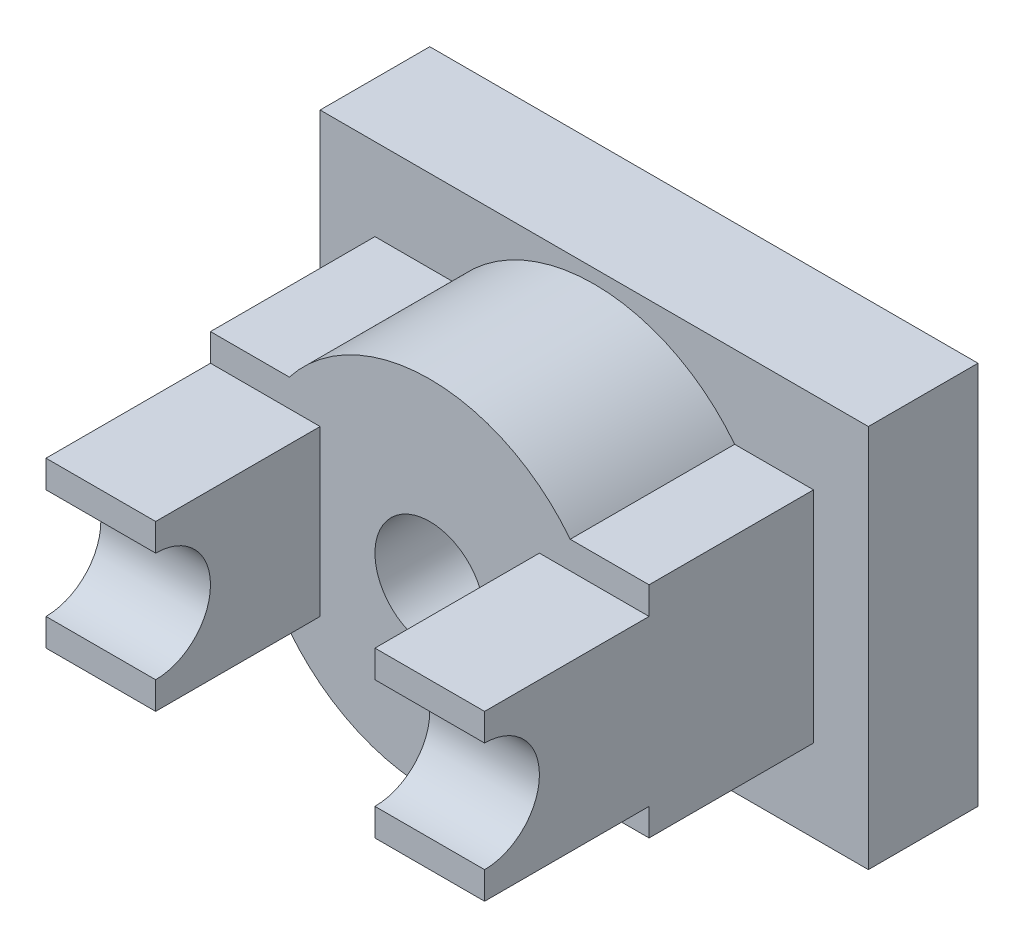
SolidWorks part; units mm, degrees
ref_plane "前基準面" through (0, 0, 0) normal (0, 0, 1) x (1, 0, 0)
ref_plane "上基準面" through (0, 0, 0) normal (0, 1, 0) x (1, 0, 0)
ref_plane "右基準面" through (0, 0, 0) normal (1, 0, 0) x (0, 0, -1)
sketch "草圖1" plane through (0, 0, 0) normal (0, 0, 1) x (1, 0, 0)
  line L1 (-50, 35) -> (50, 35)
  line L2 (-50, 35) -> (-50, -35)
  line L3 (-50, -35) -> (50, -35)
  line L4 (50, 35) -> (50, -35)
  line L5 (-50, 35) -> (50, -35) construction
  line L6 (-50, -35) -> (50, 35) construction
  point P0 (0, 0)
  dimension "D1" = 100
  dimension "D2" = 70
extrude "填料-伸長1" add sketch "草圖1" along normal blind 20
sketch "草圖2" plane through (0, 0, 20) normal (0, 0, 1) x (1, 0, 0)
  line L0 (0, 22.0024) -> (0, -51.1966) construction
  line L1 (25.6174, 20) -> (40, 20)
  line L3 (25.6174, -20) -> (40, -20)
  line L4 (40, 20) -> (40, -20)
  line L5 (-20.2803, 0) -> (55.4503, 0) construction
  line L6 (-40, 20) -> (-25.6174, 20)
  line L7 (-40, 20) -> (-40, -20)
  line L8 (-40, -20) -> (-25.6174, -20)
  circle A0 centre (0, 0) radius 10
  arc A1 (-25.6174, -20) -> (25.6174, -20) centre (0, 0) ccw
  arc A2 (25.6174, 20) -> (-25.6174, 20) centre (0, 0) ccw
  point P15 (0, 0)
  dimension "D1" = 20
  dimension "D2" = 65
  dimension "D3" = 40
  dimension "D4" = 40
  dimension "D5" = 80
extrude "填料-伸長2" add sketch "草圖2" along normal blind 30
sketch "草圖3" plane through (0, 0, 50) normal (0, 0, 1) x (1, 0, 0)
  line L0 (40, -20) -> (40, 20) construction
  line L1 (20, 15) -> (40, 15)
  line L2 (20, 15) -> (20, -15)
  line L3 (20, -15) -> (40, -15)
  line L4 (40, 15) -> (40, -15)
  line L5 (-40, 20) -> (-40, -20) construction
  line L6 (-40, 15) -> (-20, 15)
  line L7 (-40, 15) -> (-40, -15)
  line L8 (-40, -15) -> (-20, -15)
  line L9 (-20, 15) -> (-20, -15)
  line L10 (-46.8827, 0) -> (61.1968, 0) construction
  dimension "D1" = 30
  dimension "D2" = 20
  dimension "D3" = 20
  dimension "D4" = 30
extrude "填料-伸長3" add sketch "草圖3" along normal blind 30
sketch "草圖4" plane through (-40, 0, 0) normal (-1, 0, 0) x (0, 0, 1)
  line L0 (80, 15) -> (80, -15) construction
  line L1 (80, 10) -> (80, -10)
  circle A0 centre (80, 0) radius 10
  line M6 (80, -15) -> (80, 15)
  dimension "D1" = 20
extrude "除料-伸長1" cut sketch "草圖4" against normal through all contours A0 M6
